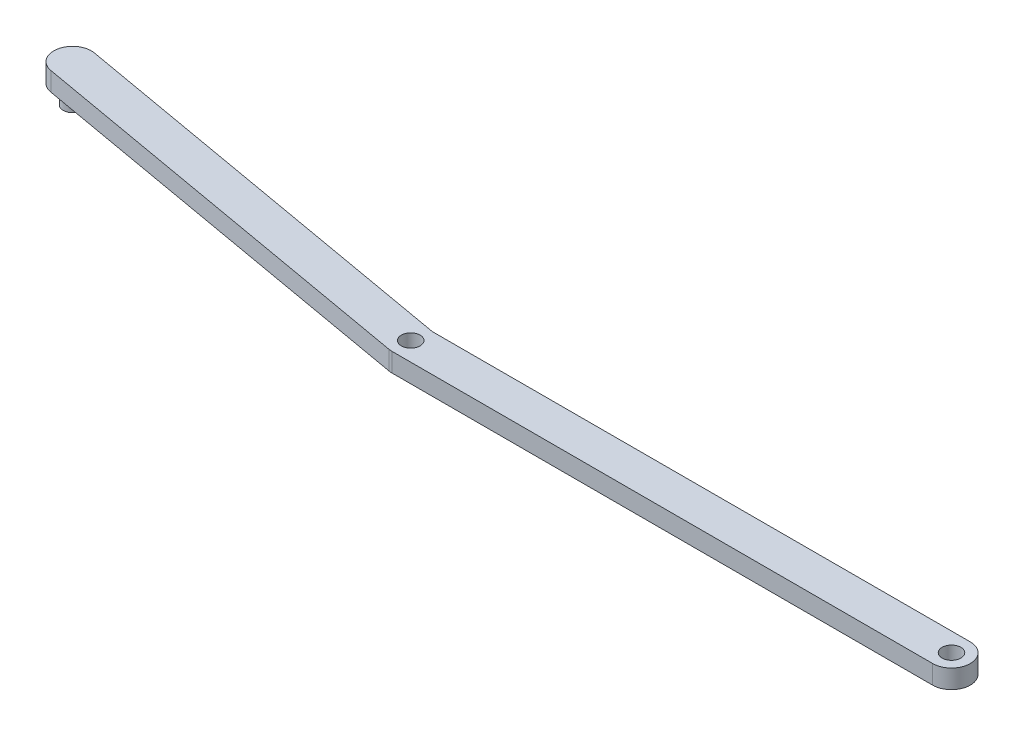
SolidWorks part; units mm, degrees
ref_plane "Front Plane" through (0, 0, 0) normal (0, 0, 1) x (1, 0, 0)
ref_plane "Top Plane" through (0, 0, 0) normal (0, 1, 0) x (1, 0, 0)
ref_plane "Right Plane" through (0, 0, 0) normal (1, 0, 0) x (0, 0, -1)
sketch "Sketch1" plane through (0, 0, 0) normal (0, 1, 0) x (1, 0, 0)
  line L0 (0, 0) -> (288, 0) construction
  line L1 (-55, 0) -> (55, 0) construction
  line L2 (0, 0) -> (-218.6273, 38.5499) construction
  line L3 (-1.7365, -9.8481) -> (-220.3638, 28.7018) construction
  line L4 (0, -10) -> (288, -10) construction
  line L5 (0, -10) -> (0, 10) construction
  line L6 (0, 10) -> (288, 10) construction
  line L7 (288, -10) -> (288, 10) construction
  line L8 (0, -10) -> (288, 10) construction
  line L9 (0, 10) -> (288, -10) construction
  line L10 (-1.7365, -9.8481) -> (1.7365, 9.8481) construction
  line L11 (-220.3638, 28.7018) -> (-216.8908, 48.398) construction
  line L12 (1.7365, 9.8481) -> (-216.8908, 48.398) construction
  line L13 (-1.7365, -9.8481) -> (-216.8908, 48.398) construction
  line L14 (-220.3638, 28.7018) -> (1.7365, 9.8481) construction
  line L15 (-216.8908, 48.398) -> (1.7365, 9.8481)
  line L16 (1.7365, 9.8481) -> (288, 10)
  line L17 (288, -10) -> (0, -10)
  line L18 (-1.7365, -9.8481) -> (-220.3638, 28.7018)
  arc A0 (-220.3638, 28.7018) -> (-216.8908, 48.398) centre (-218.6273, 38.5499) cw
  arc A1 (288, 10) -> (288, -10) centre (288, 0) cw
  arc A2 (0, -10) -> (-1.7365, -9.8481) centre (0, 0) cw
  circle A3 centre (-218.6273, 38.5499) radius 5
  circle A4 centre (0, 0) radius 5
  circle A5 centre (288, 0) radius 5
  point P5 (144, 0)
  point P12 (-109.3137, 19.2749)
  dimension "D6" = 10
  dimension "D7" = 10
  dimension "D8" = 10
  dimension "D1" = 288
  dimension "D2" = 222
  dimension "D3" = 20
  dimension "D4" = 288
  dimension "D5" = 20
extrude "Boss-Extrude1" add sketch "Sketch1" along normal mid plane 10
sketch "Sketch2" plane through (0, 0, 0) normal (0, 1, 0) x (1, 0, 0)
  circle A0 centre (-218.6273, 38.5499) radius 5
  dimension "D1" = 10
extrude "Boss-Extrude2" add sketch "Sketch2" along normal blind 5 and the other way blind 15
